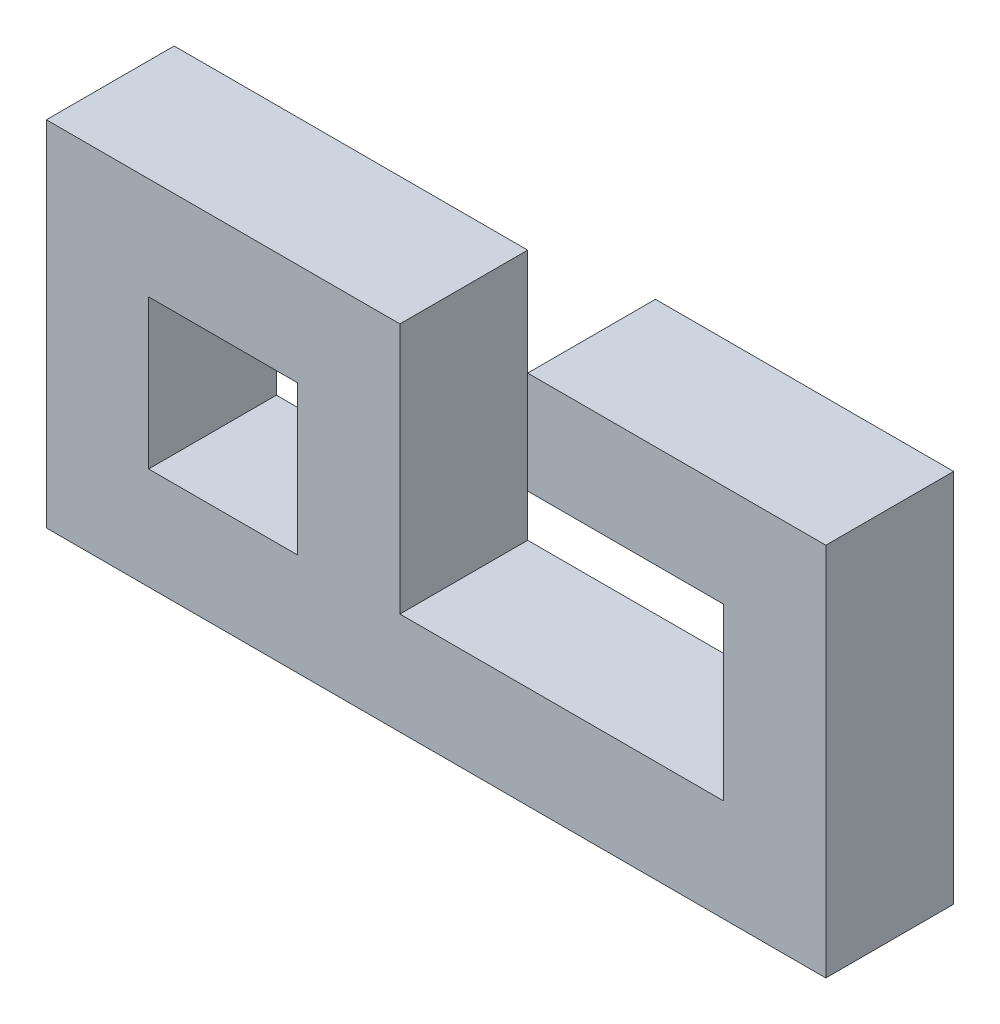
SolidWorks part; units mm, degrees
ref_plane "Alzado" through (0, 0, 0) normal (0, 0, 1) x (1, 0, 0)
ref_plane "Planta" through (0, 0, 0) normal (0, 1, 0) x (1, 0, 0)
ref_plane "Vista lateral" through (0, 0, 0) normal (1, 0, 0) x (0, 0, -1)
sketch "Croquis1" plane through (0, 0, 0) normal (0, 0, 1) x (1, 0, 0)
  line L0 (-1.859, 4.4841) -> (-1.859, -1.4159)
  line L1 (-7.759, 2.0841) -> (-4.259, 2.0841)
  line L2 (-7.759, 2.0841) -> (-7.759, -1.4159)
  line L3 (-7.759, -1.4159) -> (-4.259, -1.4159)
  line L4 (-4.259, 2.0841) -> (-4.259, -1.4159)
  line L6 (-10.159, 4.4841) -> (-10.159, -3.8159)
  line L7 (-10.159, -3.8159) -> (8.141, -3.8159)
  line L8 (8.141, 4.9841) -> (8.141, -3.8159)
  line L9 (-1.859, -1.4159) -> (5.741, -1.4159)
  line L10 (5.741, -1.4159) -> (5.741, 2.5841)
  line L11 (-10.159, 4.4841) -> (-1.859, 4.4841)
  line L12 (5.741, 2.5841) -> (1.141, 2.5841)
  line L13 (1.141, 2.5841) -> (1.141, 4.9841)
  line L14 (1.141, 4.9841) -> (8.141, 4.9841)
  dimension "D1" = 3.5
  dimension "D2" = 3.5
  dimension "D3" = 2.4
  dimension "D4" = 2.4
  dimension "D5" = 8.3
  dimension "D6" = 3
  dimension "D7" = 2.4
  dimension "D8" = 2.4
  dimension "D9" = 2.4
  dimension "D10" = 7
  dimension "D11" = 2.4
  dimension "D12" = 4
extrude "Saliente-Extruir1" add sketch "Croquis1" along normal blind 3
